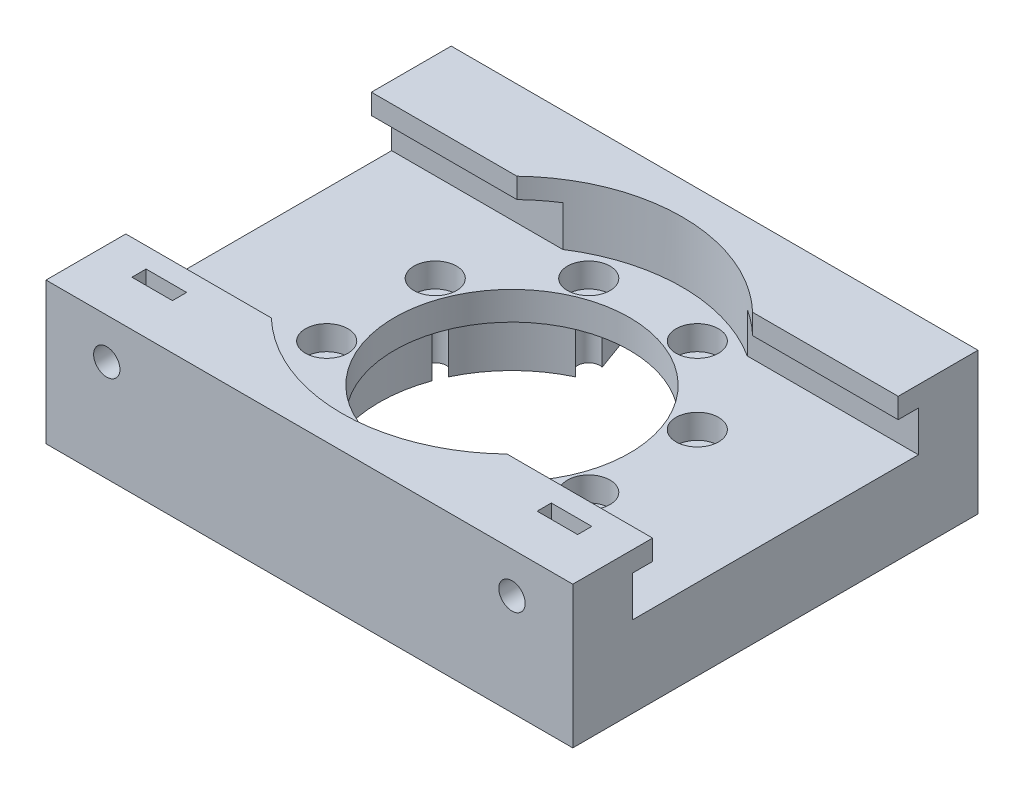
SolidWorks part; units mm, degrees
ref_plane "Front Plane" through (0, 0, 0) normal (0, 0, 1) x (1, 0, 0)
ref_plane "Top Plane" through (0, 0, 0) normal (0, 1, 0) x (1, 0, 0)
ref_plane "Right Plane" through (0, 0, 0) normal (1, 0, 0) x (0, 0, -1)
sketch "Sketch1" plane through (0, 0, 0) normal (0, 1, 0) x (1, 0, 0)
  line L0 (-122.4227, 0) -> (145.8763, 0) construction
  line L1 (-65, -50) -> (65, -50)
  line L2 (-65, -50) -> (-65, 50)
  line L3 (-65, 50) -> (65, 50)
  line L4 (65, -50) -> (65, 50)
  line L5 (0, 77.9256) -> (0, -60.4073) construction
  point P11 (-65, 0)
  dimension "D1" = 100
  dimension "D2" = 65
  dimension "D3" = 65
extrude "Boss-Extrude1" add sketch "Sketch1" along normal blind 20
sketch "Sketch11" plane through (0, 20, 0) normal (0, 1, 0) x (1, 0, 0)
  line L0 (-148.058, 0) -> (133.5933, 0) construction
  line L1 (0, 50) -> (0, -50) construction
  line L2 (0, 0) -> (-40.9461, -16.9604) construction
  circle A0 centre (0, 0) radius 35 construction
  circle A1 centre (0, 0) radius 29
  point P5 (0, 0)
  point P8 (-32.3358, -13.3939)
  point P10 (-32.3358, 13.3939)
  point P12 (-13.3939, 32.3358)
  point P24 (0, 0)
  point P25 (13.3939, 32.3358)
  point P26 (32.3358, 13.3939)
  point P27 (32.3358, -13.3939)
  point P28 (13.3939, -32.3358)
  point P29 (-13.3939, -32.3358)
  dimension "D1" = 70
  dimension "D5" = 58
  dimension "D3" = 22.5
  dimension "D2" = 8
extrude "Cut-Extrude1" cut sketch "Sketch11" against normal through all both and the other way through all
hole_wizard "CBORE for M5 Hex Head Bolt2" positions "3DSketch11" profile "Sketch14" counterbore size "M5" standard "BSI" end condition through all
sketch3d "3DSketch11"
  point P0 (-32.3358, 20, -13.3939)
  point P3 (-13.3939, 20, -32.3358)
  point P6 (13.3939, 20, -32.3358)
  point P9 (32.3358, 20, -13.3939)
  point P12 (32.3358, 20, 13.3939)
  point P15 (13.3939, 20, 32.3358)
  point P18 (-13.3939, 20, 32.3358)
  point P21 (-32.3358, 20, 13.3939)
sketch "Sketch14" plane through (-32.3358, 20, -13.3939) normal (1, 0, 0) x (0, 0, 1)
  line L0 (0, 0) -> (0, 20)
  line L1 (0, 20) -> (2.75, 20)
  line L3 (2.75, 20) -> (2.75, 6)
  line L4 (2.75, 6) -> (5.25, 6)
  line L5 (5.25, 6) -> (5.25, 0)
  line L7 (5.25, 0) -> (0, 0)
  line L11 (0, -6.35) -> (0, 107.95) construction
  dimension "Thru Hole Dia." = 5.5
  dimension "Thru Hole Depth" = 20
  dimension "C'Bore Dia." = 10.5
  dimension "C'Bore Depth" = 6
sketch "Sketch15" plane through (0, 0, 0) normal (0, 1, 0) x (1, 0, 0)
  circle A0 centre (0, 0) radius 32.75
  dimension "D1" = 65.5
extrude "Cut-Extrude2" cut sketch "Sketch15" along normal blind 13
sketch "Sketch16" plane through (0, 0, 0) normal (1, 0, 0) x (0, 0, -1)
  line L0 (0, 42.6718) -> (0, -17.6673) construction
  line L1 (-50, 20) -> (-50, 35)
  line L2 (-50, 35) -> (-30.3, 35)
  line L3 (-30.3, 35) -> (-30.3, 30)
  line L4 (-30.3, 30) -> (-35.3, 30)
  line L5 (-35.3, 30) -> (-35.3, 20)
  line L6 (-50, 20) -> (50, 20) construction
  line L7 (-35.3, 20) -> (-50, 20)
  line L8 (30.3, 35) -> (30.3, 30)
  line L9 (50, 35) -> (30.3, 35)
  line L10 (50, 20) -> (50, 35)
  line L11 (35.3, 20) -> (50, 20)
  line L12 (35.3, 30) -> (35.3, 20)
  line L13 (30.3, 30) -> (35.3, 30)
  point P8 (-32.8, 30)
  dimension "D1" = 35.3
  dimension "D2" = 10
  dimension "D3" = 5
  dimension "D4" = 5
extrude "Boss-Extrude2" add sketch "Sketch16" along normal through all and the other way through all
sketch "Sketch17" plane through (0, 20, 0) normal (0, 1, 0) x (1, 0, 0)
  circle A0 centre (0, 0) radius 42
  dimension "D1" = 84
extrude "Cut-Extrude3" cut sketch "Sketch17" along normal through all
sketch "Sketch18" plane through (0, 20, 0) normal (0, 1, 0) x (1, 0, 0)
  line L0 (-22.7576, -35.3) -> (-65, -35.3) construction
  line L1 (-55, -35.3) -> (-45, -35.3)
  line L2 (-55, -35.3) -> (-55, -38.8)
  line L3 (-55, -38.8) -> (-45, -38.8)
  line L4 (-45, -35.3) -> (-45, -38.8)
  line L5 (-65, -30.3) -> (-65, -50) construction
  line L6 (0, 57.738) -> (0, -62.9496) construction
  line L7 (55, -38.8) -> (45, -38.8)
  line L8 (45, -35.3) -> (45, -38.8)
  line L9 (55, -35.3) -> (45, -35.3)
  line L10 (55, -35.3) -> (55, -38.8)
  dimension "D1" = 3.5
  dimension "D2" = 10
  dimension "D3" = 10
extrude "Cut-Extrude4" cut sketch "Sketch18" along normal through all and the other way blind 2
sketch "Sketch19" plane through (0, 0, 0) normal (0, 0, 1) x (1, 0, 0)
  line L0 (-50, 30) -> (-50, 20) construction
  line L1 (-45, 30) -> (-55, 30) construction
  line L2 (-55, 20) -> (-45, 20) construction
  line L3 (-55, 25) -> (-45, 25) construction
  line L4 (-55, 18) -> (-55, 35) construction
  line L5 (-45, 18) -> (-45, 35) construction
  line L6 (0, 43.2429) -> (0, -15.1908) construction
  circle A0 centre (-50, 25) radius 3.25
  circle A1 centre (50, 25) radius 3.25
  point P12 (-50, 25)
  point P13 (-50, 25)
  dimension "D1" = 6.5
extrude "Cut-Extrude5" cut sketch "Sketch19" along normal through all
sketch "Sketch21" plane through (0, 0, 0) normal (0, -1, 0) x (1, 0, 0)
  line L0 (0, 0) -> (-20.3932, -56.0298)
  line L1 (0, 0) -> (0, -63.864) construction
  line L2 (0, 0) -> (20.3932, -56.0298)
  line L3 (-20.3932, -56.0298) -> (20.3932, -56.0298)
  dimension "D1" = 40
extrude "Cut-Extrude7" cut sketch "Sketch21" against normal blind 11
